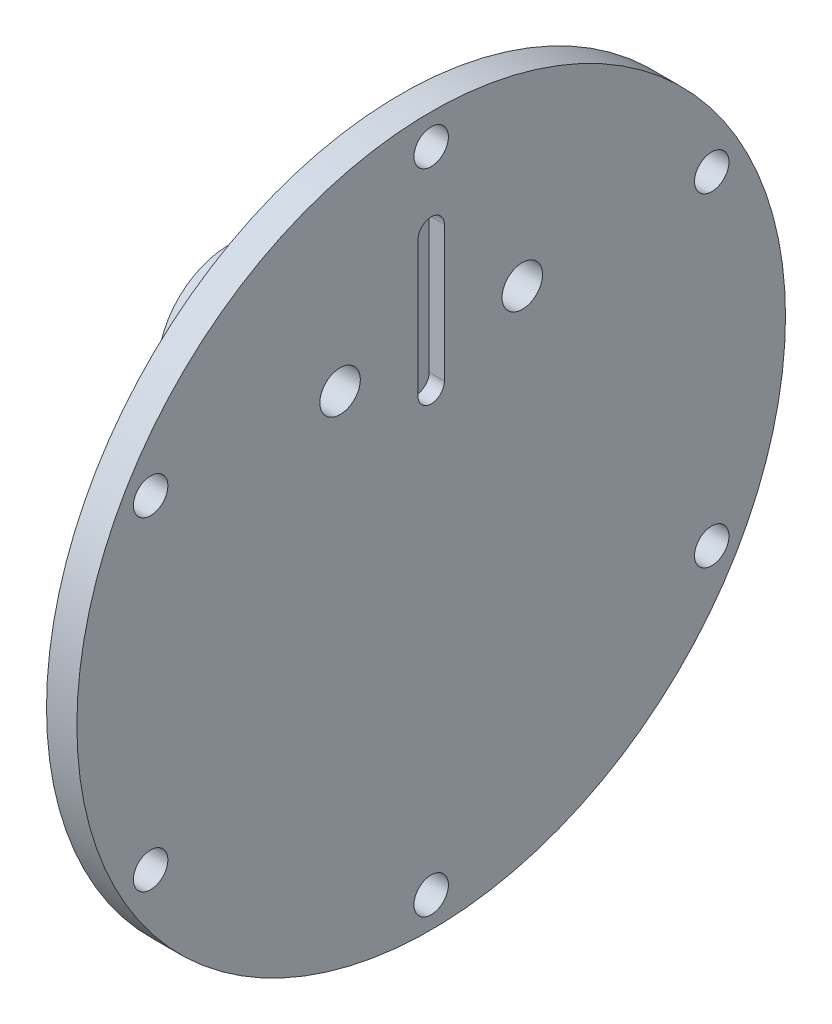
SolidWorks part; units mm, degrees
material "Copper"
ref_plane "Front Plane" through (0, 0, 0) normal (0, 0, 1) x (1, 0, 0)
ref_plane "Top Plane" through (0, 0, 0) normal (0, 1, 0) x (1, 0, 0)
ref_plane "Right Plane" through (0, 0, 0) normal (1, 0, 0) x (0, 0, -1)
sketch "Cover disk OD70 thickness3" plane through (0, 0, 0) normal (0, 0, 1) x (1, 0, 0)
  line L0 (-30, 0) -> (20, 0) construction
  line L1 (-3, 0) -> (0, 0)
  line L2 (0, 0) -> (0, 35)
  line L3 (0, 35) -> (-3, 35)
  line L4 (-3, 35) -> (-3, 0)
revolve "One-piece copper cover blank" add sketch "Cover disk OD70 thickness3" angle 360 about L0
sketch "Two integral OD14 port bosses sketch" plane through (0, 0, 0) normal (1, 0, 0) x (0, 0, -1)
  circle A0 centre (-9, 15.5885) radius 7
  circle A1 centre (9, 15.5885) radius 7
extrude "Integral port bosses rear8mm" add sketch "Two integral OD14 port bosses sketch" along normal blind 8 from offset 11
sketch "Six M3 clearance holes diameter3p4 PCD64 sketch" plane through (0, 0, 0) normal (1, 0, 0) x (0, 0, -1)
  circle A0 centre (0, 32) radius 1.7
  circle A1 centre (-27.7128, 16) radius 1.7
  circle A2 centre (-27.7128, -16) radius 1.7
  circle A3 centre (0, -32) radius 1.7
  circle A4 centre (27.7128, -16) radius 1.7
  circle A5 centre (27.7128, 16) radius 1.7
extrude "Six M3 clearance holes diameter3p4 PCD64" cut sketch "Six M3 clearance holes diameter3p4 PCD64 sketch" along normal blind 3 from offset 3
sketch "Two G1-8 tapping pilot envelopes diameter8p8 depth7 sketch" plane through (0, 0, 0) normal (1, 0, 0) x (0, 0, -1)
  circle A0 centre (-9, 15.5885) radius 4.4
  circle A1 centre (9, 15.5885) radius 4.4
extrude "Two G1-8 tapping pilot envelopes diameter8p8 depth7" cut sketch "Two G1-8 tapping pilot envelopes diameter8p8 depth7 sketch" along normal blind 7 from offset 11
sketch "Two water passages diameter4 sketch" plane through (0, 0, 0) normal (1, 0, 0) x (0, 0, -1)
  circle A0 centre (-9, 15.5885) radius 2
  circle A1 centre (9, 15.5885) radius 2
extrude "Two water passages diameter4" cut sketch "Two water passages diameter4 sketch" along normal blind 11 from offset 11
sketch "Internal bypass-strip groove length16 width2p6 depth1p5 sketch" plane through (0, 0, 0) normal (1, 0, 0) x (0, 0, -1)
  line L0 (1.3, 11.3) -> (1.3, 24.7)
  line L1 (-1.3, 24.7) -> (-1.3, 11.3)
  arc A0 (1.3, 24.7) -> (-1.3, 24.7) centre (0, 24.7) ccw
  arc A1 (-1.3, 11.3) -> (1.3, 11.3) centre (0, 11.3) ccw
extrude "Internal bypass-strip groove length16 width2p6 depth1p5" cut sketch "Internal bypass-strip groove length16 width2p6 depth1p5 sketch" along normal blind 1.5 from offset 1.5
